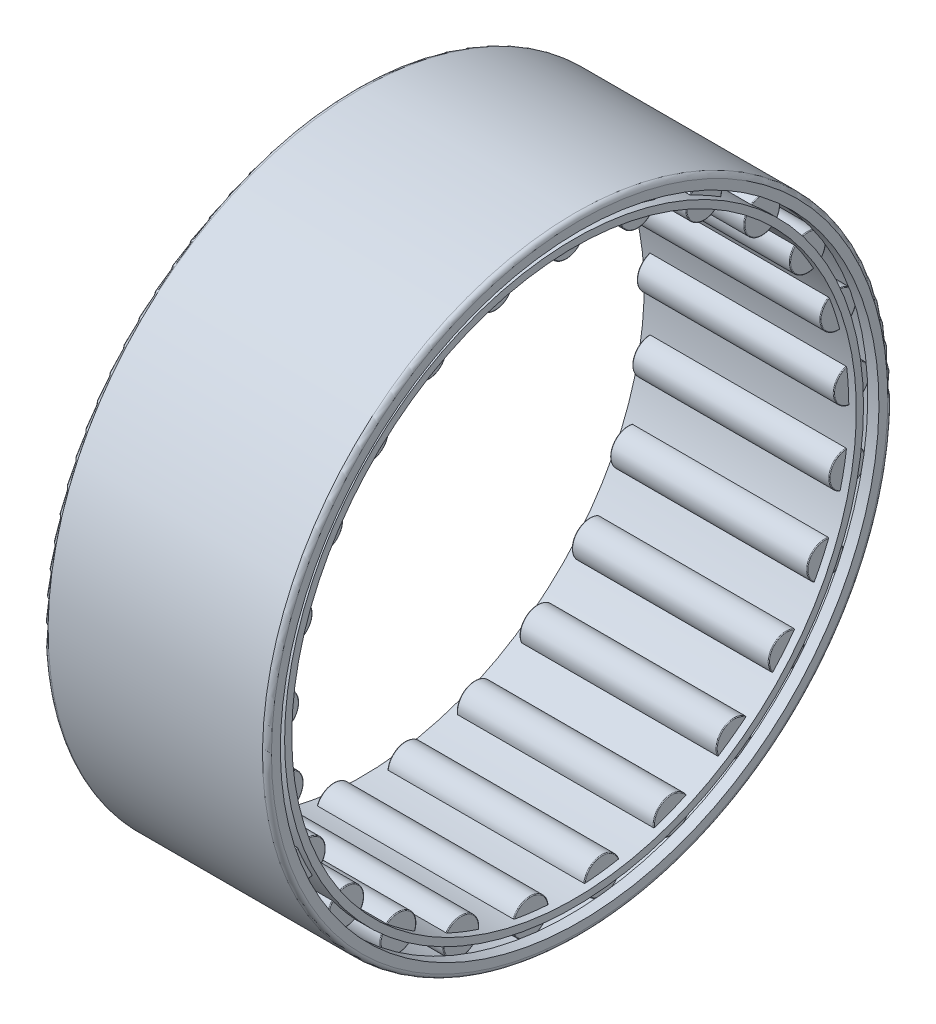
SolidWorks part; units mm, degrees
ref_plane "Plane1" through (0, 0, 0) normal (0, 0, 1) x (1, 0, 0)
ref_plane "Plane2" through (0, 0, 0) normal (0, 1, 0) x (1, 0, 0)
ref_plane "Plane3" through (0, 0, 0) normal (1, 0, 0) x (0, 0, -1)
sketch "Clipboard" plane through (0, 0, 0) normal (0, 0, 1) x (1, 0, 0)
  line L0 (-10, 0) -> (10, 0) construction
  line L1 (0, 0) -> (20.2657, -9.45)
  line L2 (0, 0) -> (36.8323, 17.1752)
  line L3 (0, 0) -> (20.2657, -9.45)
  line L4 (0, 0) -> (-76.2, -2.661)
  dimension "BallCLRad" = 40.64
  dimension "Count" = 25
  dimension "Show_count" = 25
  dimension "Max_count" = 25
  dimension "Min_count" = 2
  dimension "Bore" = 76.2
sketch "InnRacSke" plane through (0, 0, 0) normal (0, 0, 1) x (1, 0, 0)
  line L0 (-14.2875, 42.545) -> (-15.875, 42.545)
  line L1 (-15.875, 42.545) -> (-15.875, 43.815)
  line L2 (-15.24, 44.45) -> (15.24, 44.45)
  line L4 (15.875, 43.815) -> (15.875, 42.545)
  line L5 (15.875, 42.545) -> (14.2875, 42.545)
  line L6 (14.2875, 42.545) -> (14.2875, 43.18)
  line L7 (14.2875, 43.18) -> (-14.2875, 43.18)
  line L8 (-14.2875, 43.18) -> (-14.2875, 42.545)
  line L9 (-31.75, 0) -> (31.75, 0) construction
  arc A0 (-15.875, 43.815) -> (-15.24, 44.45) centre (-15.24, 43.815) cw
  arc A2 (15.24, 44.45) -> (15.875, 43.815) centre (15.24, 43.815) cw
  dimension "radius" = 0.635
  dimension "D1" = 86.36
  dimension "OD" = 88.9
  dimension "Width" = 31.75
  dimension "groove_dp" = 0.635
  dimension "Cyl_Len" = 28.575
  dimension "halfCyl" = 14.2875
revolve "Race" add sketch "InnRacSke" angle 360 about L9
sketch "RolDetSke" plane through (0, 0, 0) normal (0, 0, 1) x (1, 0, 0)
  line L0 (-14.0018, 43.0789) -> (-14.0017, 40.64)
  line L1 (-14.0017, 40.64) -> (14.0017, 40.64)
  line L2 (14.0017, 40.64) -> (14.0018, 43.0789)
  line L3 (13.9001, 43.1805) -> (-13.9001, 43.1805)
  line L4 (-28.575, 40.64) -> (28.575, 40.64) construction
  arc A0 (14.0018, 43.0789) -> (13.9001, 43.1805) centre (13.9001, 43.0789) ccw
  arc A1 (-13.9001, 43.1805) -> (-14.0018, 43.0789) centre (-13.9001, 43.0789) ccw
  dimension "Roller_radius" = 0.1016
  dimension "Roller_diameter" = 5.081
  dimension "Roller_length" = 28.0035
  dimension "RollerCLRad" = 40.64
  dimension "halfLength" = 14.0017
revolve "RollerDetailed" add sketch "RolDetSke" angle 360 about L4
ref_axis "Axis1" through (-50, 0, 0) along (1, 0, 0)
sketch "CagSpiSke" plane through (0, 0, 0) normal (0, 0, 1) x (1, 0, 0)
  line L0 (15.0812, 40.1319) -> (15.0812, 41.1481)
  line L1 (15.0812, 41.1481) -> (-15.0813, 41.1481)
  line L2 (-15.0813, 41.1481) -> (-15.0813, 40.1319)
  line L3 (-15.0813, 40.1319) -> (15.0812, 40.1319)
  line L4 (-31.75, 0) -> (31.75, 0) construction
  dimension "Cage_width" = 30.1625
  dimension "D2" = 80.2638
  dimension "Cage_thickness" = 1.0162
  dimension "halfWidth" = 15.0813
revolve "CageSpine" add sketch "CagSpiSke" angle 360 about L4
pattern_circular "RollersDetailed" count 25 every 14.4 about axis through (-50, 0, 0) along (1, 0, 0) of "RollerDetailed"
sketch "RolSimSke" plane through (0, 0, 0) normal (0, 0, 1) x (1, 0, 0)
  line L0 (-25.4, 0) -> (25.4, 0) construction
  line L2 (-13.9001, 43.181) -> (13.9001, 43.181)
  line L3 (-14.0018, 43.0794) -> (-14.0018, 38.2016)
  line L4 (-13.9001, 38.1) -> (13.9001, 38.1)
  line L5 (14.0017, 43.0794) -> (14.0017, 38.2016)
  arc A0 (-14.0018, 38.2016) -> (-13.9001, 38.1) centre (-13.9001, 38.2016) ccw
  arc A1 (-13.9001, 43.181) -> (-14.0018, 43.0794) centre (-13.9001, 43.0794) ccw
  arc A2 (14.0017, 43.0794) -> (13.9001, 43.181) centre (13.9001, 43.0794) ccw
  arc A3 (13.9001, 38.1) -> (14.0017, 38.2016) centre (13.9001, 38.2016) ccw
  point P10 (-14.0018, 38.1)
  point P15 (14.0017, 43.181)
  point P18 (14.0017, 38.1)
  dimension "Bore" = 76.2
  dimension "Roller_diameter" = 5.081
  dimension "Roller_length" = 28.0035
  dimension "D1" = 0.1016
  dimension "halfWidth" = 14.0017
revolve "RollersSimplified" [suppressed] add sketch "RolSimSke" angle 360 about L0
equation "\"BallCLRad@Clipboard\" =  ( \"D1@InnRacSke\" + \"Bore@Clipboard\" )  / 4"
equation "\"RollerCLRad@RolDetSke\" = \"BallCLRad@Clipboard\""
equation "\"halfCyl@InnRacSke\" = \"Cyl_Len@InnRacSke\" / 2"
equation "\"Roller_length@RolDetSke\" = \"Cyl_Len@InnRacSke\" * .98"
equation "\"halfLength@RolDetSke\" = \"Roller_length@RolDetSke\" / 2"
equation "\"Roller_diameter@RolDetSke\" =  ( \"D1@InnRacSke\" - \"Bore@Clipboard\" )  / 2 + .001"
equation "\"Roller_radius@RolDetSke\" = \"Roller_diameter@RolDetSke\" / 50"
equation "\"Cage_width@CagSpiSke\" =  ( \"Cyl_Len@InnRacSke\" + \"Width@InnRacSke\" )  / 2"
equation "\"halfWidth@CagSpiSke\" = \"Cage_width@CagSpiSke\" / 2"
equation "\"Cage_thickness@CagSpiSke\"  = \"Roller_diameter@RolDetSke\" / 5"
equation "\"D2@CagSpiSke\" =  \"RollerCLRad@RolDetSke\" * 2 - \"Cage_thickness@CagSpiSke\""
equation "\"Roller_length@RolSimSke\" = \"Cyl_Len@InnRacSke\" * .98"
equation "\"halfWidth@RolSimSke\" = \"Roller_length@RolSimSke\" / 2"
equation "\"D1@RolSimSke\" = \"Roller_radius@RolDetSke\""
equation "\"Roller_diameter@RolSimSke\" =  ( \"D1@InnRacSke\" - \"Bore@Clipboard\" )  / 2 + .001"
equation "\"Bore@RolSimSke\" = \"Bore@Clipboard\""
equation "\"Max_count@Clipboard\" = int( 3.14159265 / atn(( \"Roller_diameter@RolDetSke\" / 2) / sqr( \"RollerCLRad@RolDetSke\"  *  \"RollerCLRad@RolDetSke\" - ( \"Roller_diameter@RolDetSke\" / 2) *  ( \"Roller_diameter@RolDetSke\" / 2))))"
equation "\"Max_count@Clipboard\" = ((sgn( \"Max_count@Clipboard\" - \"Count@Clipboard\" )-1)*( \"Max_count@Clipboard\" - \"Count@Clipboard\" ))/-2+ \"Count@Clipboard\""
equation "\"Count@RollersDetailed\" = int( \"Show_count@Clipboard\" ) "
equation "\"Count@RollersDetailed\" = ((sgn( \"Count@RollersDetailed\" - \"Max_count@Clipboard\" )-1)*( \"Count@RollersDetailed\" - \"Max_count@Clipboard\" ))/-2+ \"Max_count@Clipboard\""
equation "\"Count@RollersDetailed\" = ((sgn( \"Count@RollersDetailed\" - \"Min_count@Clipboard\" )+1)*( \"Count@RollersDetailed\" - \"Min_count@Clipboard\"))/2 +\"Min_count@Clipboard\""
equation "\"Angle@RollersDetailed\" = 360.0 / \"Max_count@Clipboard\""
equation "\"Angle@CageSpine\" =  \"Angle@RollersDetailed\" * ( \"Count@RollersDetailed\" -1 + int( \"Count@RollersDetailed\" / \"Max_count@Clipboard\" ) )  + 0.001 -  int( \"Count@RollersDetailed\" / \"Max_count@Clipboard\" ) * 0.001"
equation "\"Angle@CageSpine\" =  \"Angle@CageSpine\" * int( \"Min_count@Clipboard\" / 2) + int(1 / \"Min_count@Clipboard\")  * 0.001"
